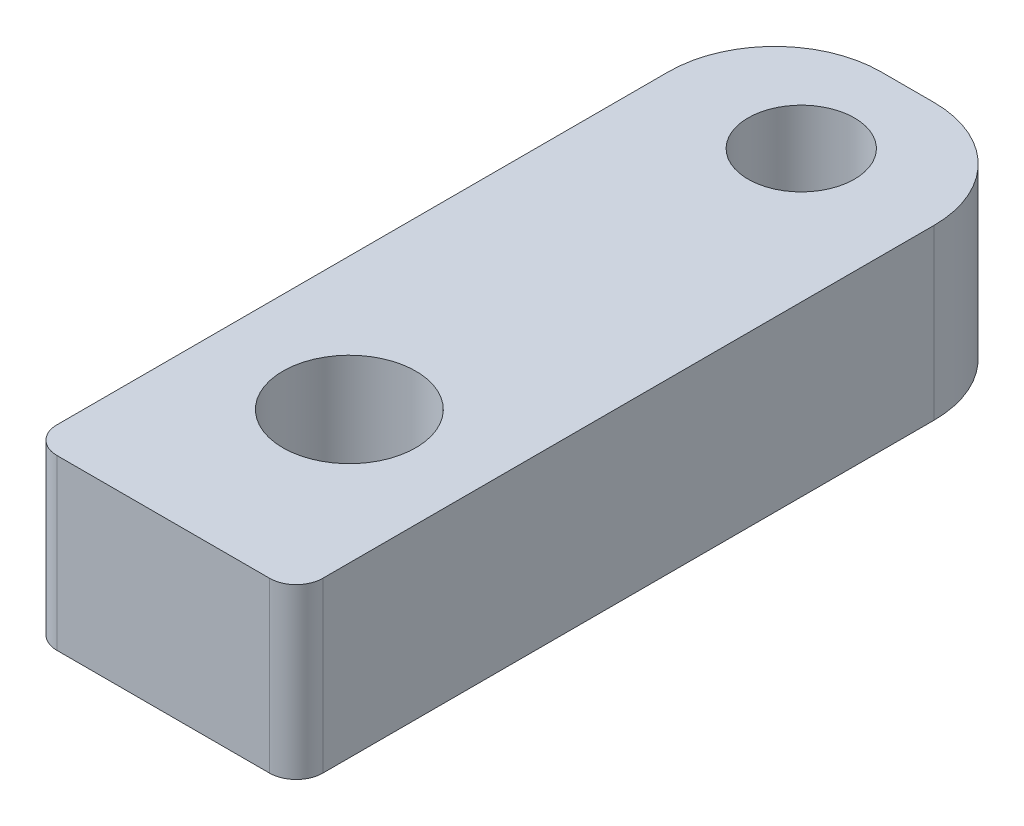
SolidWorks part; units mm, degrees
material "Copper"
ref_plane "Front Plane" through (0, 0, 0) normal (0, 0, 1) x (1, 0, 0)
ref_plane "Top Plane" through (0, 0, 0) normal (0, 1, 0) x (1, 0, 0)
ref_plane "Right Plane" through (0, 0, 0) normal (1, 0, 0) x (0, 0, -1)
sketch "Sketch2" plane through (0, 0, 0) normal (0, 1, 0) x (1, 0, 0)
  line L0 (0, 0) -> (2.5, 0) construction
  line L1 (-2.5, -7) -> (2.5, -7)
  line L2 (-2.5, -7) -> (-2.5, 7)
  line L3 (-2.5, 7) -> (2.5, 7)
  line L4 (2.5, -7) -> (2.5, 7)
  line L5 (-2.5, -7) -> (2.5, 7) construction
  line L6 (-2.5, 7) -> (2.5, -7) construction
  circle A1 centre (0, 5) radius 1
  point P0 (0, 0)
  point P6 (0, 3.0086)
  point P8 (0, -3.5)
  dimension "D3" = 3.5
  dimension "D4" = 2
  dimension "D1" = 5
  dimension "D2" = 3.5
  dimension "D5" = 2
extrude "Boss-Extrude1" add sketch "Sketch2" against normal blind 3.175
hole_wizard "M3x0.5 Tapped Hole1" positions "Sketch3" profile "Sketch4" tap size "M3x0.5" standard "ANSI Metric" end condition through all
sketch "Sketch3" plane through (0, 0, 0) normal (0, 1, 0) x (1, 0, 0)
  point P0 (0, -3.5)
sketch "Sketch4" plane through (0, 0, 3.5) normal (1, 0, 0) x (0, 0, 1)
  line L0 (0, 0) -> (0, 3.175)
  line L1 (0, 3.175) -> (1.25, 3.175)
  line L2 (1.25, 3.175) -> (1.25, 0)
  line L5 (1.25, 0) -> (0, 0)
  line L11 (0, -6.35) -> (0, 107.95) construction
  dimension "Thru Tap Drill Dia." = 2.5
  dimension "Thru Tap Drill Depth" = 3.175
cosmetic thread "Hole Thread1" parameters "D2"=3
fillet "Fillet1" radius 2 2 edges at (-2.5, -1.5875, -7) (2.5, -1.5875, -7)
fillet "Fillet2" radius 0.5 2 edges at (-2.5, -1.5875, 7) (2.5, -1.5875, 7)
